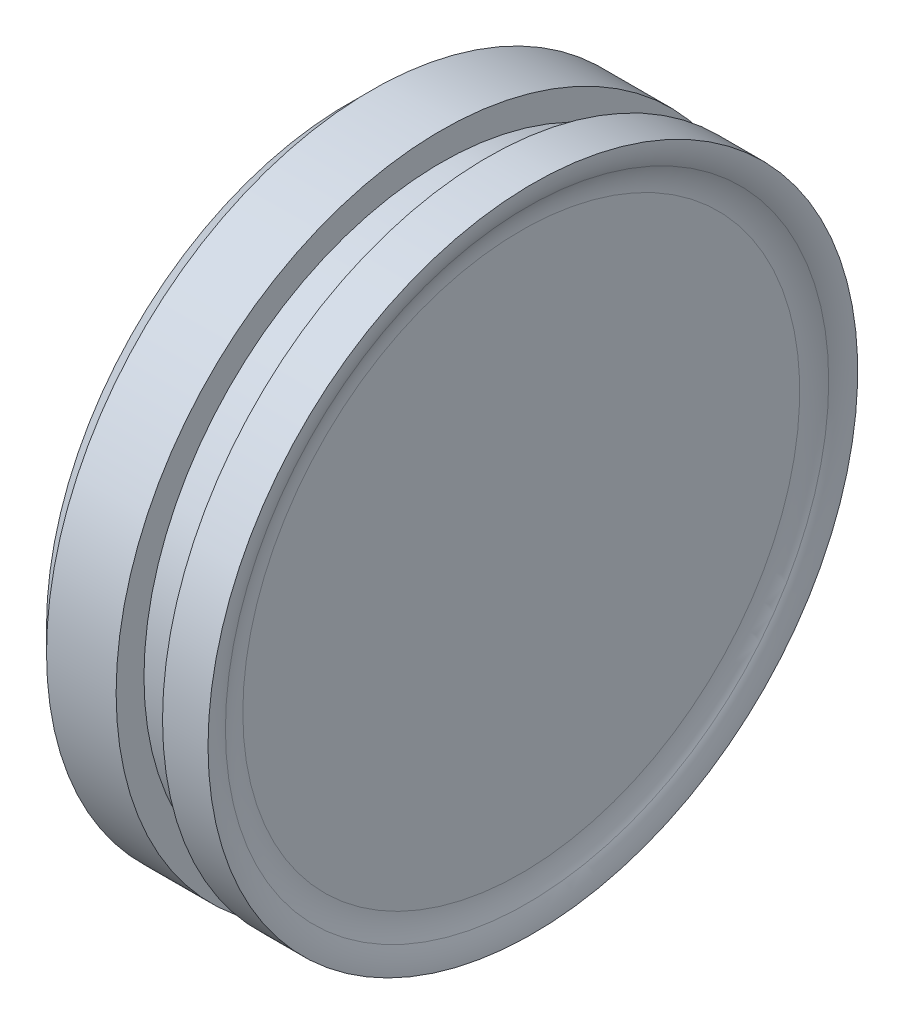
SolidWorks part; units mm, degrees
material "3003 Alloy"
ref_plane "Front Plane" through (0, 0, 0) normal (0, 0, 1) x (1, 0, 0)
ref_plane "Top Plane" through (0, 0, 0) normal (0, 1, 0) x (1, 0, 0)
ref_plane "Right Plane" through (0, 0, 0) normal (1, 0, 0) x (0, 0, -1)
sketch "Sketch1" plane through (0, 0, 0) normal (0, 0, 1) x (1, 0, 0)
  line L0 (0, 0) -> (0, 7)
  line L1 (0, 7) -> (2, 7)
  line L2 (0, 0) -> (3.73, 0)
  line L3 (3.73, 0) -> (3.73, 6)
  line L4 (3.98, 5.8423) -> (3.98, 3.0468) construction
  line L5 (2, 7) -> (2, 0) construction
  line L6 (2, 7) -> (2, 6.4)
  line L7 (2, 6.4) -> (3, 6.4)
  line L8 (3, 6.4) -> (3, 7)
  line L9 (3, 7) -> (3.98, 7)
  arc A0 (3.98, 7) -> (3.855, 6.5) centre (2.9175, 7) cw
  arc A1 (3.73, 6) -> (3.855, 6.5) centre (4.7925, 6) cw
  dimension "D1" = 7
  dimension "D2" = 3.98
  dimension "D3" = 0.5
  dimension "D4" = 0.5
  dimension "D5" = 2
  dimension "D6" = 1
  dimension "D7" = 0.6
  dimension "D8" = 2
revolve "Revolve1" add sketch "Sketch1" angle 360 about L2
chamfer "Chamfer1" distance 0.5 angle 45 1 edges at (0, 0, 7)
